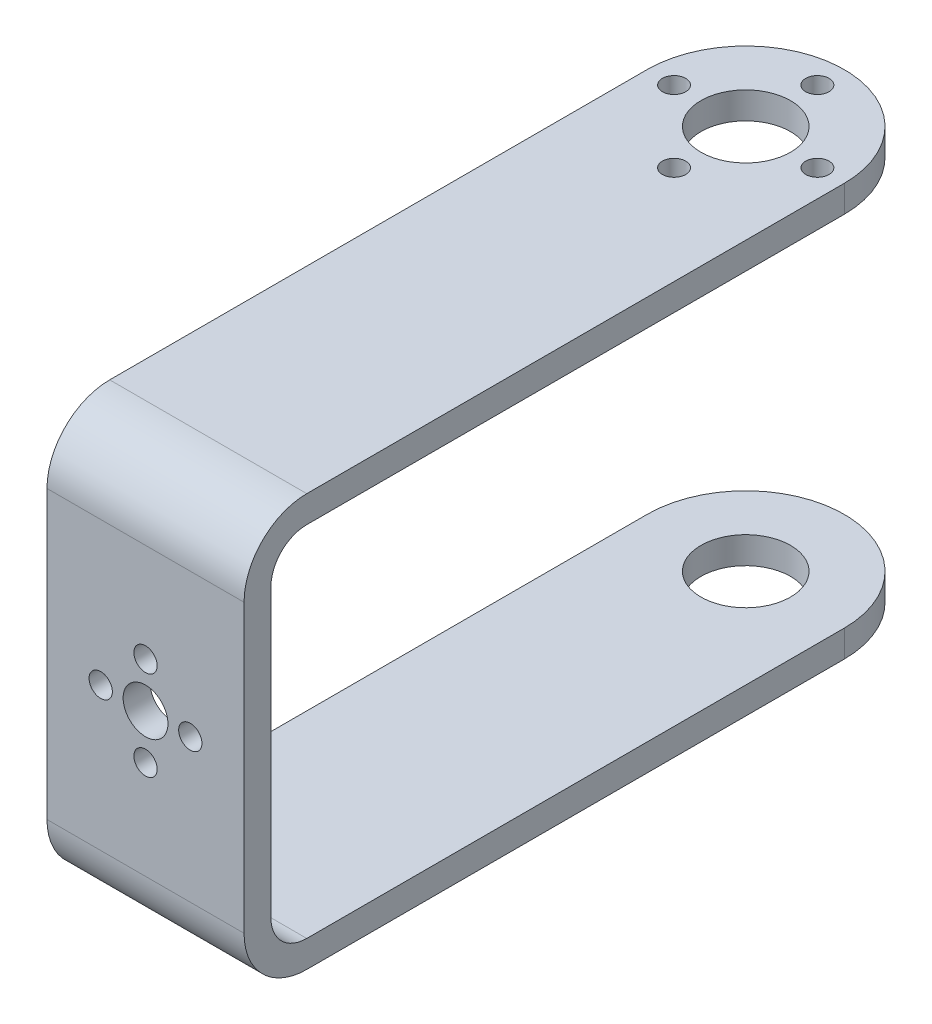
SolidWorks part; units mm, degrees
ref_plane "Front Plane" through (0, 0, 0) normal (0, 0, 1) x (1, 0, 0)
ref_plane "Top Plane" through (0, 0, 0) normal (0, 1, 0) x (1, 0, 0)
ref_plane "Right Plane" through (0, 0, 0) normal (1, 0, 0) x (0, 0, -1)
sketch "Sketch1" plane through (0, 0, 0) normal (0, 1, 0) x (1, 0, 0)
  line L5 (-11, 0) -> (11, 0)
  line L6 (-11, 0) -> (-11, -60)
  line L7 (-11, -60) -> (11, -60)
  line L8 (11, 0) -> (11, -60)
  circle A0 centre (0, 0) radius 11
  circle A1 centre (0, 0) radius 8 construction
  circle A2 centre (0, 8) radius 1.3
  circle A3 centre (8, 0) radius 1.3
  circle A4 centre (0, -8) radius 1.3
  circle A5 centre (-8, 0) radius 1.3
  circle A6 centre (0, 0) radius 5
  point P19 (0, 0)
  dimension "D1" = 16
  dimension "D3" = 2.6
  dimension "D4" = 10
  dimension "D5" = 22
  dimension "D6" = 22
  dimension "D7" = 60
  dimension "D2" = 4
extrude "Boss-Extrude1" add sketch "Sketch1" along normal blind 3 contours A0 L6 L7 L8 | A6 L5 A5 A0 A3 A4 | A6 L5 A3 A0 A5 A2
sketch "Sketch2" plane through (11, 0, 0) normal (1, 0, 0) x (0, 0, -1)
  line L0 (-60, 3) -> (-60, 0)
  line L1 (-67, -4) -> (-64, -4)
  line L2 (-67, -4) -> (-67, -36)
  line L3 (-67, -36) -> (-64, -36)
  line L4 (-64, -4) -> (-64, -36)
  line L5 (-60, -40) -> (-60, -43)
  arc A0 (-60, 0) -> (-64, -4) centre (-60, -4) ccw
  arc A1 (-60, 3) -> (-67, -4) centre (-60, -4) ccw
  arc A2 (-67, -36) -> (-60, -43) centre (-60, -36) ccw
  arc A3 (-64, -36) -> (-60, -40) centre (-60, -36) ccw
  point P12 (0, 0)
  point P13 (0, 0)
  line M4 (-60, 3) -> (-60, 0)
  dimension "D1" = 4
  dimension "D2" = 4
  dimension "D3" = 4
  dimension "D4" = 4
  dimension "D5" = 32
extrude "Boss-Extrude2" add sketch "Sketch2" against normal up to surface (22 mm away) contours L4 L1 L2 L3 | A1 L1 A0 M4 | A3 L3 A2 L5 up to face at (-11, 1.5, 30)
ref_plane "Plane1" through (0, -40, 0) normal (0, -1, 0) x (-1, 0, 0)
sketch "Sketch6" plane through (0, -40, 0) normal (0, -1, 0) x (-1, 0, 0)
  line L1 (-11, 0) -> (11, 0)
  line L2 (-11, 0) -> (-11, -60)
  line L3 (-11, -60) -> (11, -60)
  line L4 (11, 0) -> (11, -60)
  circle A1 centre (0, 0) radius 11
  circle A2 centre (0, 0) radius 5
extrude "Boss-Extrude3" add sketch "Sketch6" along normal blind 3 contours A1 L2 L3 L4 | A2 L1 A1 | A2 L1 A1
sketch "Sketch7" plane through (0, 0, 67) normal (0, 0, 1) x (1, 0, 0)
  line L0 (0, -4) -> (0, -36) construction
  line L1 (-11, -4) -> (11, -4) construction
  line L2 (-11, -36) -> (11, -36) construction
  line L3 (11, -20) -> (-11, -20) construction
  line L4 (11, -4) -> (11, -36) construction
  line L5 (-11, -36) -> (-11, -4) construction
  circle A0 centre (0, -20) radius 2.5
  circle A1 centre (0, -20) radius 5
  circle A2 centre (5, -20) radius 1.3
  circle A3 centre (-5, -20) radius 1.3
  circle A4 centre (0, -25) radius 1.3
  circle A5 centre (0, -15) radius 1.3
  dimension "D1" = 2.6
  dimension "D2" = 5
  dimension "D3" = 10
extrude "Cut-Extrude1" cut sketch "Sketch7" against normal up to surface (3 mm away) contours A0 | A1 A2 | A1 A2 | A1 A4 | A1 A4 | A3 A1 | A3 A1 | A1 A5 | A1 A5
equation "\"D6@Sketch1\"=\"D5@Sketch1\""
